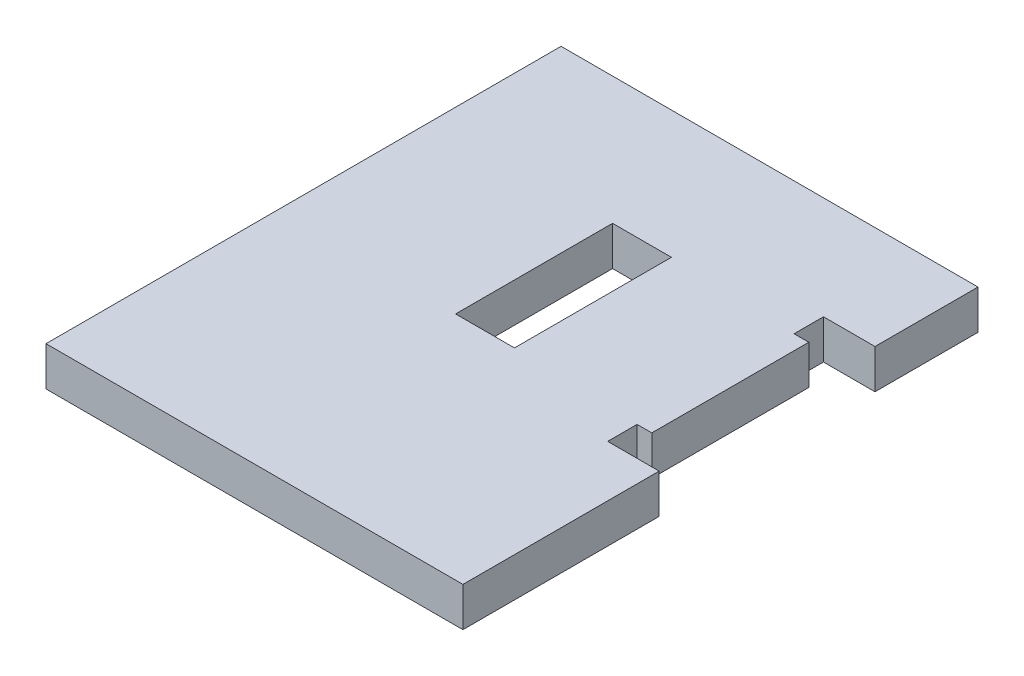
SolidWorks part; units mm, degrees
ref_plane "前视基准面" through (0, 0, 0) normal (0, 0, 1) x (1, 0, 0)
ref_plane "上视基准面" through (0, 0, 0) normal (0, 1, 0) x (1, 0, 0)
ref_plane "右视基准面" through (0, 0, 0) normal (1, 0, 0) x (0, 0, -1)
sketch "草图1" plane through (0, 0, 0) normal (0, 1, 0) x (1, 0, 0)
  line L1 (-17, 21) -> (0, 21)
  line L2 (-17, 21) -> (-17, 0)
  line L3 (-17, 0) -> (0, 0)
  line L4 (0, 21) -> (0, 0)
extrude "凸台-拉伸1" add sketch "草图1" along normal blind 1.6
sketch "草图2" plane through (0, 1.6, 0) normal (0, 1, 0) x (1, 0, 0)
  line L1 (-9.7, 15.8) -> (-7.3, 15.8)
  line L2 (-9.7, 15.8) -> (-9.7, 9.4)
  line L3 (-9.7, 9.4) -> (-7.3, 9.4)
  line L4 (-7.3, 15.8) -> (-7.3, 9.4)
extrude "切除-拉伸1" cut sketch "草图2" against normal blind 10
sketch "草图3" plane through (0, 1.6, 0) normal (0, 1, 0) x (1, 0, 0)
  line L0 (0, 0) -> (0, 21) construction
  line L1 (0, 16.8) -> (-1.5, 16.8)
  line L2 (0, 16.8) -> (0, 8)
  line L3 (0, 8) -> (-1.5, 8)
  line L5 (-1.5, 8) -> (-2.1, 8)
  line L6 (-2.1, 8) -> (-2.1, 9.2)
  line L7 (-2.1, 9.2) -> (-1.5, 9.2)
  line L8 (-1.5, 16.8) -> (-2.1, 16.8)
  line L9 (-2.1, 16.8) -> (-2.1, 15.6)
  line L10 (-2.1, 15.6) -> (-1.5, 15.6)
  line L11 (-1.5, 15.6) -> (-1.5, 9.2)
extrude "切除-拉伸2" cut sketch "草图3" against normal blind 10
